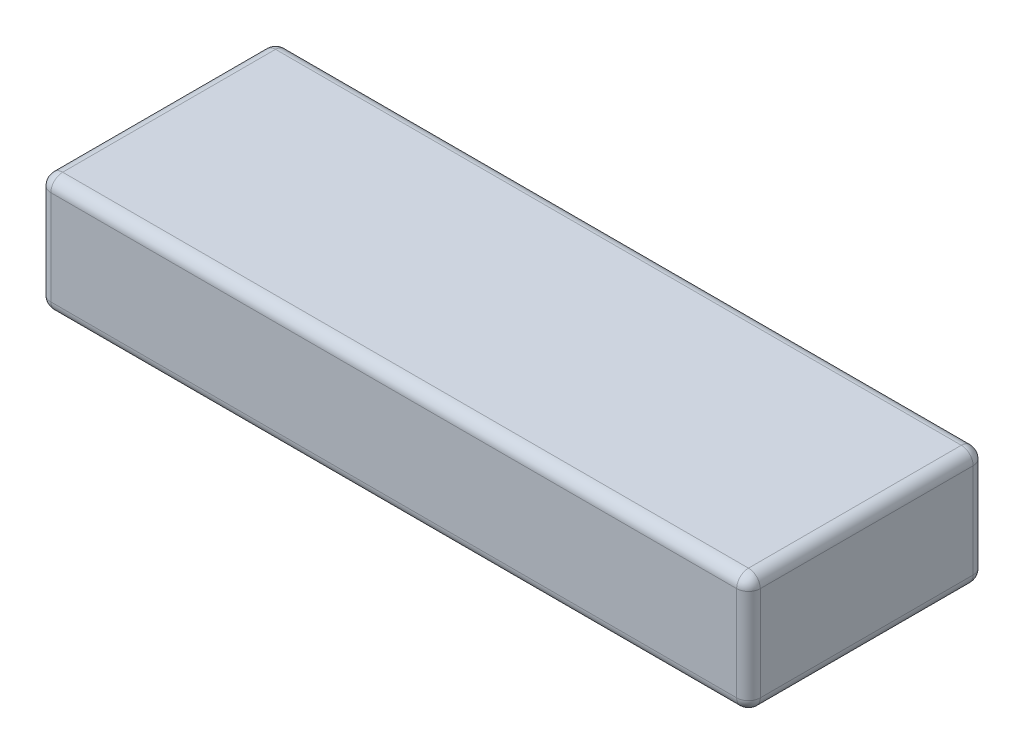
SolidWorks part; units mm, degrees
material "Nickel"
ref_plane "Front Plane" through (0, 0, 0) normal (0, 0, 1) x (1, 0, 0)
ref_plane "Top Plane" through (0, 0, 0) normal (0, 1, 0) x (1, 0, 0)
ref_plane "Right Plane" through (0, 0, 0) normal (1, 0, 0) x (0, 0, -1)
sketch "Sketch1" plane through (0, 0, 0) normal (0, 1, 0) x (1, 0, 0)
  line L1 (-30, 10) -> (30, 10)
  line L2 (-30, 10) -> (-30, -10)
  line L3 (-30, -10) -> (30, -10)
  line L4 (30, 10) -> (30, -10)
  line L5 (-30, 10) -> (30, -10) construction
  line L6 (-30, -10) -> (30, 10) construction
  point P0 (0, 0)
  dimension "D1" = 60
  dimension "D2" = 20
extrude "Boss-Extrude1" add sketch "Sketch1" along normal mid plane 10
fillet "Fillet1" radius 1 12 edges at (0, -5, 10) (0, 5, 10) (-30, 5, 0) (-30, 0, 10) (-30, -5, 0) (0, 5, -10) (-30, 0, -10) (0, -5, -10) (30, 0, 10) (30, 5, 0) (30, 0, -10) (30, -5, 0)
